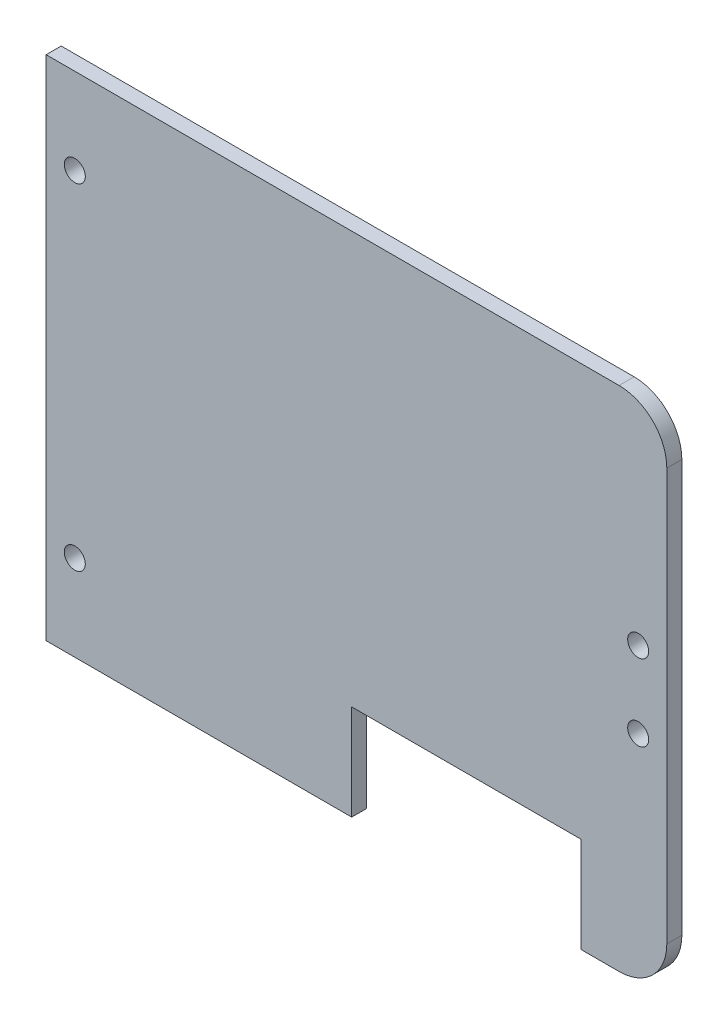
SolidWorks part; units mm, degrees
ref_plane "Front Plane" through (0, 0, 0) normal (0, 0, 1) x (1, 0, 0)
ref_plane "Top Plane" through (0, 0, 0) normal (0, 1, 0) x (1, 0, 0)
ref_plane "Right Plane" through (0, 0, 0) normal (1, 0, 0) x (0, 0, -1)
sketch "BPR2 PCB Outline" plane through (0, 0, 0) normal (0, 0, 1) x (1, 0, 0)
  line L0 (0, 0) -> (0, 53.15)
  line L1 (0, 53.15) -> (60, 53.15)
  line L2 (65, 48.15) -> (65, 5)
  line L3 (60, 0) -> (56, 0)
  line L4 (56, 0) -> (56, 10)
  line L5 (56, 10) -> (32, 10)
  line L6 (32, 10) -> (32, 0)
  line L7 (32, 0) -> (0, 0)
  arc A0 (65, 48.15) -> (60, 53.15) centre (60, 48.15) ccw
  arc A1 (60, 0) -> (65, 5) centre (60, 5) ccw
  circle A2 centre (3, 9) radius 1.1
  circle A3 centre (62, 22.575) radius 1.1
  circle A4 centre (3, 44.15) radius 1.1
  circle A5 centre (62, 30.575) radius 1.1
sketch "23" plane through (0, 0, 0) normal (0, 0, 1) x (1, 0, 0)
  point P0 (0, 0)
sketch "48" plane through (0, 0, 0) normal (0, 0, 1) x (1, 0, 0)
  line L0 (2, 15) -> (3.0323, 15)
  line L1 (4.0323, 15) -> (5.0645, 15)
  line L2 (6.0645, 15) -> (7.0968, 15)
  line L3 (8.0968, 15) -> (9.129, 15)
  line L4 (10.129, 15) -> (11.1613, 15)
  line L5 (12.1613, 15) -> (13.1935, 15)
  line L6 (14.1935, 15) -> (15.2258, 15)
  line L7 (16.2258, 15) -> (17.2581, 15)
  line L8 (18.2581, 15) -> (19.2903, 15)
  line L9 (20.2903, 15) -> (21.3226, 15)
  line L10 (22.3226, 15) -> (23.3548, 15)
  line L11 (24.3548, 15) -> (25.3871, 15)
  line L12 (26.3871, 15) -> (27.4194, 15)
  line L13 (28.4194, 15) -> (29.4516, 15)
  line L14 (30.4516, 15) -> (31.4839, 15)
  line L15 (32.4839, 15) -> (33.5161, 15)
  line L16 (34.5161, 15) -> (35.5484, 15)
  line L17 (36.5484, 15) -> (37.5806, 15)
  line L18 (38.5806, 15) -> (39.6129, 15)
  line L19 (40.6129, 15) -> (41.6452, 15)
  line L20 (42.6452, 15) -> (43.6774, 15)
  line L21 (44.6774, 15) -> (45.7097, 15)
  line L22 (46.7097, 15) -> (47.7419, 15)
  line L23 (48.7419, 15) -> (49.7742, 15)
  line L24 (50.7742, 15) -> (51.8065, 15)
  line L25 (52.8065, 15) -> (53.8387, 15)
  line L26 (54.8387, 15) -> (55.871, 15)
  line L27 (56.871, 15) -> (57.9032, 15)
  line L28 (58.9032, 15) -> (59.9355, 15)
  line L29 (60.9355, 15) -> (61.9677, 15)
  line L30 (62.9677, 15) -> (64, 15)
  line L31 (2, 16.575) -> (3.0323, 16.575)
  line L32 (4.0323, 16.575) -> (5.0645, 16.575)
  line L33 (6.0645, 16.575) -> (7.0968, 16.575)
  line L34 (8.0968, 16.575) -> (9.129, 16.575)
  line L35 (10.129, 16.575) -> (11.1613, 16.575)
  line L36 (12.1613, 16.575) -> (13.1935, 16.575)
  line L37 (14.1935, 16.575) -> (15.2258, 16.575)
  line L38 (16.2258, 16.575) -> (17.2581, 16.575)
  line L39 (18.2581, 16.575) -> (19.2903, 16.575)
  line L40 (20.2903, 16.575) -> (21.3226, 16.575)
  line L41 (22.3226, 16.575) -> (23.3548, 16.575)
  line L42 (24.3548, 16.575) -> (25.3871, 16.575)
  line L43 (26.3871, 16.575) -> (27.4194, 16.575)
  line L44 (28.4194, 16.575) -> (29.4516, 16.575)
  line L45 (30.4516, 16.575) -> (31.4839, 16.575)
  line L46 (32.4839, 16.575) -> (33.5161, 16.575)
  line L47 (34.5161, 16.575) -> (35.5484, 16.575)
  line L48 (36.5484, 16.575) -> (37.5806, 16.575)
  line L49 (38.5806, 16.575) -> (39.6129, 16.575)
  line L50 (40.6129, 16.575) -> (41.6452, 16.575)
  line L51 (42.6452, 16.575) -> (43.6774, 16.575)
  line L52 (44.6774, 16.575) -> (45.7097, 16.575)
  line L53 (46.7097, 16.575) -> (47.7419, 16.575)
  line L54 (48.7419, 16.575) -> (49.7742, 16.575)
  line L55 (50.7742, 16.575) -> (51.8065, 16.575)
  line L56 (52.8065, 16.575) -> (53.8387, 16.575)
  line L57 (54.8387, 16.575) -> (55.871, 16.575)
  line L58 (56.871, 16.575) -> (57.9032, 16.575)
  line L59 (58.9032, 16.575) -> (59.9355, 16.575)
  line L60 (60.9355, 16.575) -> (61.9677, 16.575)
  line L61 (62.9677, 16.575) -> (64, 16.575)
  line L62 (2, 36.575) -> (3.0323, 36.575)
  line L63 (4.0323, 36.575) -> (5.0645, 36.575)
  line L64 (6.0645, 36.575) -> (7.0968, 36.575)
  line L65 (8.0968, 36.575) -> (9.129, 36.575)
  line L66 (10.129, 36.575) -> (11.1613, 36.575)
  line L67 (12.1613, 36.575) -> (13.1935, 36.575)
  line L68 (14.1935, 36.575) -> (15.2258, 36.575)
  line L69 (16.2258, 36.575) -> (17.2581, 36.575)
  line L70 (18.2581, 36.575) -> (19.2903, 36.575)
  line L71 (20.2903, 36.575) -> (21.3226, 36.575)
  line L72 (22.3226, 36.575) -> (23.3548, 36.575)
  line L73 (24.3548, 36.575) -> (25.3871, 36.575)
  line L74 (26.3871, 36.575) -> (27.4194, 36.575)
  line L75 (28.4194, 36.575) -> (29.4516, 36.575)
  line L76 (30.4516, 36.575) -> (31.4839, 36.575)
  line L77 (32.4839, 36.575) -> (33.5161, 36.575)
  line L78 (34.5161, 36.575) -> (35.5484, 36.575)
  line L79 (36.5484, 36.575) -> (37.5806, 36.575)
  line L80 (38.5806, 36.575) -> (39.6129, 36.575)
  line L81 (40.6129, 36.575) -> (41.6452, 36.575)
  line L82 (42.6452, 36.575) -> (43.6774, 36.575)
  line L83 (44.6774, 36.575) -> (45.7097, 36.575)
  line L84 (46.7097, 36.575) -> (47.7419, 36.575)
  line L85 (48.7419, 36.575) -> (49.7742, 36.575)
  line L86 (50.7742, 36.575) -> (51.8065, 36.575)
  line L87 (52.8065, 36.575) -> (53.8387, 36.575)
  line L88 (54.8387, 36.575) -> (55.871, 36.575)
  line L89 (56.871, 36.575) -> (57.9032, 36.575)
  line L90 (58.9032, 36.575) -> (59.9355, 36.575)
  line L91 (60.9355, 36.575) -> (61.9677, 36.575)
  line L92 (62.9677, 36.575) -> (64, 36.575)
  line L93 (2, 38.15) -> (3.0385, 38.15)
  line L94 (4.0385, 38.15) -> (5.0769, 38.15)
  line L95 (6.0769, 38.15) -> (7.1154, 38.15)
  line L96 (8.1154, 38.15) -> (9.1538, 38.15)
  line L97 (10.1538, 38.15) -> (11.1923, 38.15)
  line L98 (12.1923, 38.15) -> (13.2308, 38.15)
  line L99 (14.2308, 38.15) -> (15.2692, 38.15)
  line L100 (16.2692, 38.15) -> (17.3077, 38.15)
  line L101 (18.3077, 38.15) -> (19.3462, 38.15)
  line L102 (20.3462, 38.15) -> (21.3846, 38.15)
  line L103 (22.3846, 38.15) -> (23.4231, 38.15)
  line L104 (24.4231, 38.15) -> (25.4615, 38.15)
  line L105 (26.4615, 38.15) -> (27.5, 38.15)
  line L106 (27.5, 38.15) -> (28.525, 38.15)
  line L107 (29.525, 38.15) -> (30.55, 38.15)
  line L108 (31.55, 38.15) -> (32.575, 38.15)
  line L109 (33.575, 38.15) -> (34.6, 38.15)
  line L110 (35.6, 38.15) -> (36.625, 38.15)
  line L111 (37.625, 38.15) -> (38.65, 38.15)
  line L112 (39.65, 38.15) -> (40.675, 38.15)
  line L113 (41.675, 38.15) -> (42.7, 38.15)
  line L114 (43.7, 38.15) -> (44.725, 38.15)
  line L115 (45.725, 38.15) -> (46.75, 38.15)
  line L116 (47.75, 38.15) -> (48.775, 38.15)
  line L117 (49.775, 38.15) -> (50.8, 38.15)
  line L118 (50.8, 38.15) -> (51.8286, 38.15)
  line L119 (52.8286, 38.15) -> (53.8571, 38.15)
  line L120 (54.8571, 38.15) -> (55.8857, 38.15)
  line L121 (56.8857, 38.15) -> (57.9143, 38.15)
  line L122 (58.9143, 38.15) -> (59.9429, 38.15)
  line L123 (60.9429, 38.15) -> (61.9714, 38.15)
  line L124 (62.9714, 38.15) -> (64, 38.15)
  line L125 (27.5, 38.15) -> (27.5, 41.14)
  line L126 (27.5, 41.8214) -> (27.5, 41.9586)
  line L127 (27.5, 42.64) -> (27.5, 45.63)
  line L128 (27.5, 46.3114) -> (27.5, 46.4487)
  line L129 (27.5, 47.13) -> (27.5, 50.12)
  line L130 (27.5, 50.8013) -> (27.5, 50.9387)
  line L131 (27.5, 51.62) -> (27.5, 54.61)
  line L132 (27.5, 54.61) -> (30.1333, 54.61)
  line L133 (30.8147, 54.61) -> (30.952, 54.61)
  line L134 (31.6333, 54.61) -> (34.2667, 54.61)
  line L135 (34.948, 54.61) -> (35.0853, 54.61)
  line L136 (35.7667, 54.61) -> (38.4, 54.61)
  line L137 (39.0814, 54.61) -> (39.2187, 54.61)
  line L138 (39.9, 54.61) -> (42.5333, 54.61)
  line L139 (43.2147, 54.61) -> (43.352, 54.61)
  line L140 (44.0333, 54.61) -> (46.6667, 54.61)
  line L141 (47.348, 54.61) -> (47.4853, 54.61)
  line L142 (48.1667, 54.61) -> (50.8, 54.61)
  line L143 (50.8, 54.61) -> (50.82, 54.61)
  line L144 (27.5, -1.46) -> (30.1333, -1.46)
  line L145 (30.8147, -1.46) -> (30.952, -1.46)
  line L146 (31.6333, -1.46) -> (34.2667, -1.46)
  line L147 (34.948, -1.46) -> (35.0853, -1.46)
  line L148 (35.7667, -1.46) -> (38.4, -1.46)
  line L149 (39.0814, -1.46) -> (39.2187, -1.46)
  line L150 (39.9, -1.46) -> (42.5333, -1.46)
  line L151 (43.2147, -1.46) -> (43.352, -1.46)
  line L152 (44.0333, -1.46) -> (46.6667, -1.46)
  line L153 (47.348, -1.46) -> (47.4853, -1.46)
  line L154 (48.1667, -1.46) -> (50.8, -1.46)
  line L155 (50.8, -1.46) -> (50.82, -1.46)
  line L156 (27.5, 14.82) -> (27.5, 11.875)
  line L157 (27.5, 11.1936) -> (27.5, 11.0564)
  line L158 (27.5, 10.375) -> (27.5, 7.43)
  line L159 (27.5, 6.7487) -> (27.5, 6.6114)
  line L160 (27.5, 5.93) -> (27.5, 2.985)
  line L161 (27.5, 2.3037) -> (27.5, 2.1663)
  line L162 (27.5, 1.485) -> (27.5, -1.46)
  line L163 (50.8, 38.15) -> (50.8, 41.14)
  line L164 (50.8, 41.8214) -> (50.8, 41.9586)
  line L165 (50.8, 42.64) -> (50.8, 45.63)
  line L166 (50.8, 46.3114) -> (50.8, 46.4487)
  line L167 (50.8, 47.13) -> (50.8, 50.12)
  line L168 (50.8, 50.8013) -> (50.8, 50.9387)
  line L169 (50.8, 51.62) -> (50.8, 54.61)
  line L170 (50.8, 14.82) -> (50.8, 11.875)
  line L171 (50.8, 11.1936) -> (50.8, 11.0564)
  line L172 (50.8, 10.375) -> (50.8, 7.43)
  line L173 (50.8, 6.7487) -> (50.8, 6.6114)
  line L174 (50.8, 5.93) -> (50.8, 2.985)
  line L175 (50.8, 2.3037) -> (50.8, 2.1663)
  line L176 (50.8, 1.485) -> (50.8, -1.46)
  arc A0 (27.5317, 41.14) -> (27.4683, 41.14) centre (27.5, 41.14) ccw
  arc A1 (27.4683, 38.15) -> (27.5317, 38.15) centre (27.5, 38.15) ccw
  arc A2 (27.5317, 41.9586) -> (27.4683, 41.9586) centre (27.5, 41.9586) ccw
  arc A3 (27.4683, 41.8214) -> (27.5317, 41.8214) centre (27.5, 41.8214) ccw
  arc A4 (27.5317, 45.63) -> (27.4683, 45.63) centre (27.5, 45.63) ccw
  arc A5 (27.4683, 42.64) -> (27.5317, 42.64) centre (27.5, 42.64) ccw
  arc A6 (27.5317, 46.4487) -> (27.4683, 46.4487) centre (27.5, 46.4487) ccw
  arc A7 (27.4683, 46.3114) -> (27.5317, 46.3114) centre (27.5, 46.3114) ccw
  arc A8 (27.5317, 50.12) -> (27.4683, 50.12) centre (27.5, 50.12) ccw
  arc A9 (27.4683, 47.13) -> (27.5317, 47.13) centre (27.5, 47.13) ccw
  arc A10 (27.5317, 50.9387) -> (27.4683, 50.9387) centre (27.5, 50.9387) ccw
  arc A11 (27.4683, 50.8013) -> (27.5317, 50.8013) centre (27.5, 50.8013) ccw
  arc A12 (27.5317, 54.61) -> (27.4683, 54.61) centre (27.5, 54.61) ccw
  arc A13 (27.4683, 51.62) -> (27.5317, 51.62) centre (27.5, 51.62) ccw
  arc A14 (30.1333, 54.5782) -> (30.1333, 54.6418) centre (30.1333, 54.61) ccw
  arc A15 (27.5, 54.6418) -> (27.5, 54.5782) centre (27.5, 54.61) ccw
  arc A16 (30.952, 54.5782) -> (30.952, 54.6418) centre (30.952, 54.61) ccw
  arc A17 (30.8147, 54.6418) -> (30.8147, 54.5782) centre (30.8147, 54.61) ccw
  arc A18 (34.2667, 54.5782) -> (34.2667, 54.6418) centre (34.2667, 54.61) ccw
  arc A19 (31.6333, 54.6418) -> (31.6333, 54.5782) centre (31.6333, 54.61) ccw
  arc A20 (35.0853, 54.5782) -> (35.0853, 54.6418) centre (35.0853, 54.61) ccw
  arc A21 (34.948, 54.6418) -> (34.948, 54.5782) centre (34.948, 54.61) ccw
  arc A22 (38.4, 54.5782) -> (38.4, 54.6418) centre (38.4, 54.61) ccw
  arc A23 (35.7667, 54.6418) -> (35.7667, 54.5782) centre (35.7667, 54.61) ccw
  arc A24 (39.2187, 54.5782) -> (39.2187, 54.6418) centre (39.2187, 54.61) ccw
  arc A25 (39.0814, 54.6418) -> (39.0814, 54.5782) centre (39.0814, 54.61) ccw
  arc A26 (42.5333, 54.5782) -> (42.5333, 54.6418) centre (42.5333, 54.61) ccw
  arc A27 (39.9, 54.6418) -> (39.9, 54.5782) centre (39.9, 54.61) ccw
  arc A28 (43.352, 54.5782) -> (43.352, 54.6418) centre (43.352, 54.61) ccw
  arc A29 (43.2147, 54.6418) -> (43.2147, 54.5782) centre (43.2147, 54.61) ccw
  arc A30 (46.6667, 54.5782) -> (46.6667, 54.6418) centre (46.6667, 54.61) ccw
  arc A31 (44.0333, 54.6418) -> (44.0333, 54.5782) centre (44.0333, 54.61) ccw
  arc A32 (47.4853, 54.5782) -> (47.4853, 54.6418) centre (47.4853, 54.61) ccw
  arc A33 (47.348, 54.6418) -> (47.348, 54.5782) centre (47.348, 54.61) ccw
  arc A34 (50.8, 54.5782) -> (50.8, 54.6418) centre (50.8, 54.61) ccw
  arc A35 (48.1667, 54.6418) -> (48.1667, 54.5782) centre (48.1667, 54.61) ccw
  arc A36 (50.82, 54.5782) -> (50.82, 54.6418) centre (50.82, 54.61) ccw
  arc A37 (50.8, 54.6418) -> (50.8, 54.5782) centre (50.8, 54.61) ccw
  arc A38 (30.1333, -1.4917) -> (30.1333, -1.4283) centre (30.1333, -1.46) ccw
  arc A39 (27.5, -1.4283) -> (27.5, -1.4917) centre (27.5, -1.46) ccw
  arc A40 (30.952, -1.4917) -> (30.952, -1.4283) centre (30.952, -1.46) ccw
  arc A41 (30.8147, -1.4283) -> (30.8147, -1.4917) centre (30.8147, -1.46) ccw
  arc A42 (34.2667, -1.4917) -> (34.2667, -1.4283) centre (34.2667, -1.46) ccw
  arc A43 (31.6333, -1.4283) -> (31.6333, -1.4917) centre (31.6333, -1.46) ccw
  arc A44 (35.0853, -1.4917) -> (35.0853, -1.4283) centre (35.0853, -1.46) ccw
  arc A45 (34.948, -1.4283) -> (34.948, -1.4917) centre (34.948, -1.46) ccw
  arc A46 (38.4, -1.4917) -> (38.4, -1.4283) centre (38.4, -1.46) ccw
  arc A47 (35.7667, -1.4283) -> (35.7667, -1.4917) centre (35.7667, -1.46) ccw
  arc A48 (39.2187, -1.4917) -> (39.2187, -1.4283) centre (39.2187, -1.46) ccw
  arc A49 (39.0814, -1.4283) -> (39.0814, -1.4917) centre (39.0814, -1.46) ccw
  arc A50 (42.5333, -1.4917) -> (42.5333, -1.4283) centre (42.5333, -1.46) ccw
  arc A51 (39.9, -1.4283) -> (39.9, -1.4917) centre (39.9, -1.46) ccw
  arc A52 (43.352, -1.4917) -> (43.352, -1.4283) centre (43.352, -1.46) ccw
  arc A53 (43.2147, -1.4283) -> (43.2147, -1.4917) centre (43.2147, -1.46) ccw
  arc A54 (46.6667, -1.4917) -> (46.6667, -1.4283) centre (46.6667, -1.46) ccw
  arc A55 (44.0333, -1.4283) -> (44.0333, -1.4917) centre (44.0333, -1.46) ccw
  arc A56 (47.4853, -1.4917) -> (47.4853, -1.4283) centre (47.4853, -1.46) ccw
  arc A57 (47.348, -1.4283) -> (47.348, -1.4917) centre (47.348, -1.46) ccw
  arc A58 (50.8, -1.4917) -> (50.8, -1.4283) centre (50.8, -1.46) ccw
  arc A59 (48.1667, -1.4283) -> (48.1667, -1.4917) centre (48.1667, -1.46) ccw
  arc A60 (50.82, -1.4917) -> (50.82, -1.4283) centre (50.82, -1.46) ccw
  arc A61 (50.8, -1.4283) -> (50.8, -1.4917) centre (50.8, -1.46) ccw
  arc A62 (27.4683, 11.875) -> (27.5317, 11.875) centre (27.5, 11.875) ccw
  arc A63 (27.5317, 14.82) -> (27.4683, 14.82) centre (27.5, 14.82) ccw
  arc A64 (27.4683, 11.0564) -> (27.5317, 11.0564) centre (27.5, 11.0564) ccw
  arc A65 (27.5317, 11.1936) -> (27.4683, 11.1936) centre (27.5, 11.1936) ccw
  arc A66 (27.4683, 7.43) -> (27.5317, 7.43) centre (27.5, 7.43) ccw
  arc A67 (27.5317, 10.375) -> (27.4683, 10.375) centre (27.5, 10.375) ccw
  arc A68 (27.4683, 6.6114) -> (27.5317, 6.6114) centre (27.5, 6.6114) ccw
  arc A69 (27.5317, 6.7487) -> (27.4683, 6.7487) centre (27.5, 6.7487) ccw
  arc A70 (27.4683, 2.985) -> (27.5317, 2.985) centre (27.5, 2.985) ccw
  arc A71 (27.5317, 5.93) -> (27.4683, 5.93) centre (27.5, 5.93) ccw
  arc A72 (27.4683, 2.1663) -> (27.5317, 2.1663) centre (27.5, 2.1663) ccw
  arc A73 (27.5317, 2.3037) -> (27.4683, 2.3037) centre (27.5, 2.3037) ccw
  arc A74 (27.4683, -1.46) -> (27.5317, -1.46) centre (27.5, -1.46) ccw
  arc A75 (27.5317, 1.485) -> (27.4683, 1.485) centre (27.5, 1.485) ccw
  arc A76 (50.8318, 41.14) -> (50.7683, 41.14) centre (50.8, 41.14) ccw
  arc A77 (50.7683, 38.15) -> (50.8318, 38.15) centre (50.8, 38.15) ccw
  arc A78 (50.8318, 41.9586) -> (50.7683, 41.9586) centre (50.8, 41.9586) ccw
  arc A79 (50.7683, 41.8214) -> (50.8318, 41.8214) centre (50.8, 41.8214) ccw
  arc A80 (50.8318, 45.63) -> (50.7683, 45.63) centre (50.8, 45.63) ccw
  arc A81 (50.7683, 42.64) -> (50.8318, 42.64) centre (50.8, 42.64) ccw
  arc A82 (50.8318, 46.4487) -> (50.7683, 46.4487) centre (50.8, 46.4487) ccw
  arc A83 (50.7683, 46.3114) -> (50.8318, 46.3114) centre (50.8, 46.3114) ccw
  arc A84 (50.8318, 50.12) -> (50.7683, 50.12) centre (50.8, 50.12) ccw
  arc A85 (50.7683, 47.13) -> (50.8318, 47.13) centre (50.8, 47.13) ccw
  arc A86 (50.8318, 50.9387) -> (50.7683, 50.9387) centre (50.8, 50.9387) ccw
  arc A87 (50.7683, 50.8013) -> (50.8318, 50.8013) centre (50.8, 50.8013) ccw
  arc A88 (50.8318, 54.61) -> (50.7683, 54.61) centre (50.8, 54.61) ccw
  arc A89 (50.7683, 51.62) -> (50.8318, 51.62) centre (50.8, 51.62) ccw
  arc A90 (50.7683, 11.875) -> (50.8318, 11.875) centre (50.8, 11.875) ccw
  arc A91 (50.8318, 14.82) -> (50.7683, 14.82) centre (50.8, 14.82) ccw
  arc A92 (50.7683, 11.0564) -> (50.8318, 11.0564) centre (50.8, 11.0564) ccw
  arc A93 (50.8318, 11.1936) -> (50.7683, 11.1936) centre (50.8, 11.1936) ccw
  arc A94 (50.7683, 7.43) -> (50.8318, 7.43) centre (50.8, 7.43) ccw
  arc A95 (50.8318, 10.375) -> (50.7683, 10.375) centre (50.8, 10.375) ccw
  arc A96 (50.7683, 6.6114) -> (50.8318, 6.6114) centre (50.8, 6.6114) ccw
  arc A97 (50.8318, 6.7487) -> (50.7683, 6.7487) centre (50.8, 6.7487) ccw
  arc A98 (50.7683, 2.985) -> (50.8318, 2.985) centre (50.8, 2.985) ccw
  arc A99 (50.8318, 5.93) -> (50.7683, 5.93) centre (50.8, 5.93) ccw
  arc A100 (50.7683, 2.1663) -> (50.8318, 2.1663) centre (50.8, 2.1663) ccw
  arc A101 (50.8318, 2.3037) -> (50.7683, 2.3037) centre (50.8, 2.3037) ccw
  arc A102 (50.7683, -1.46) -> (50.8318, -1.46) centre (50.8, -1.46) ccw
  arc A103 (50.8318, 1.485) -> (50.7683, 1.485) centre (50.8, 1.485) ccw
extrude "Boss-Extrude1" add sketch "BPR2 PCB Outline" against normal blind 1.5748
sketch "Label BPR Inside" plane through (0, 0, 0) normal (0, 0, 1) x (1, 0, 0)
  line L0 (0, 53.15) -> (0, 0) construction
  line L1 (60, 53.15) -> (0, 53.15) construction
  text T0 "BPR INSIDE" font "Courier New" height 0.25
  dimension "D1" = 0.5
  dimension "D2" = 1
sketch "Label BPR Outside" plane through (0, 0, -1.5748) normal (0, 0, 1) x (1, 0, 0)
  line L1 (0, 53.15) -> (0, 0) construction
  line L2 (60, 53.15) -> (0, 53.15) construction
  text T0 "BPR OUTSIDE" font "Courier New" height 0.25
  point P9 (4.6331, 52.057)
  point P10 (1.47, 53.0821)
  dimension "D1" = 3
  dimension "D2" = 1
